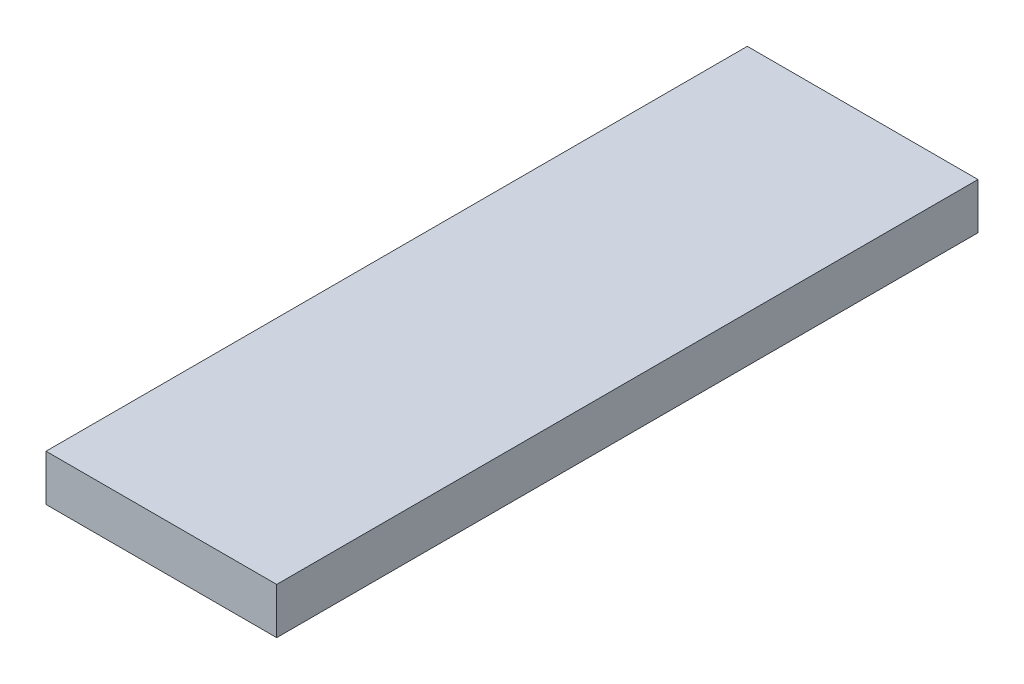
SolidWorks part; units mm, degrees
ref_plane "Plan de face" through (0, 0, 0) normal (0, 0, 1) x (1, 0, 0)
ref_plane "Plan de dessus" through (0, 0, 0) normal (0, 1, 0) x (1, 0, 0)
ref_plane "Plan de droite" through (0, 0, 0) normal (1, 0, 0) x (0, 0, -1)
sketch "Esquisse1" plane through (0, 0, 0) normal (0, 1, 0) x (1, 0, 0)
  line L1 (-50, -152) -> (50, -152)
  line L2 (-50, -152) -> (-50, 152)
  line L3 (-50, 152) -> (50, 152)
  line L4 (50, -152) -> (50, 152)
  line L5 (-50, -152) -> (50, 152) construction
  line L6 (-50, 152) -> (50, -152) construction
  point P0 (0, 0)
  dimension "D1" = 100
  dimension "D2" = 304
extrude "Boss.-Extru.1" add sketch "Esquisse1" along normal blind 20
